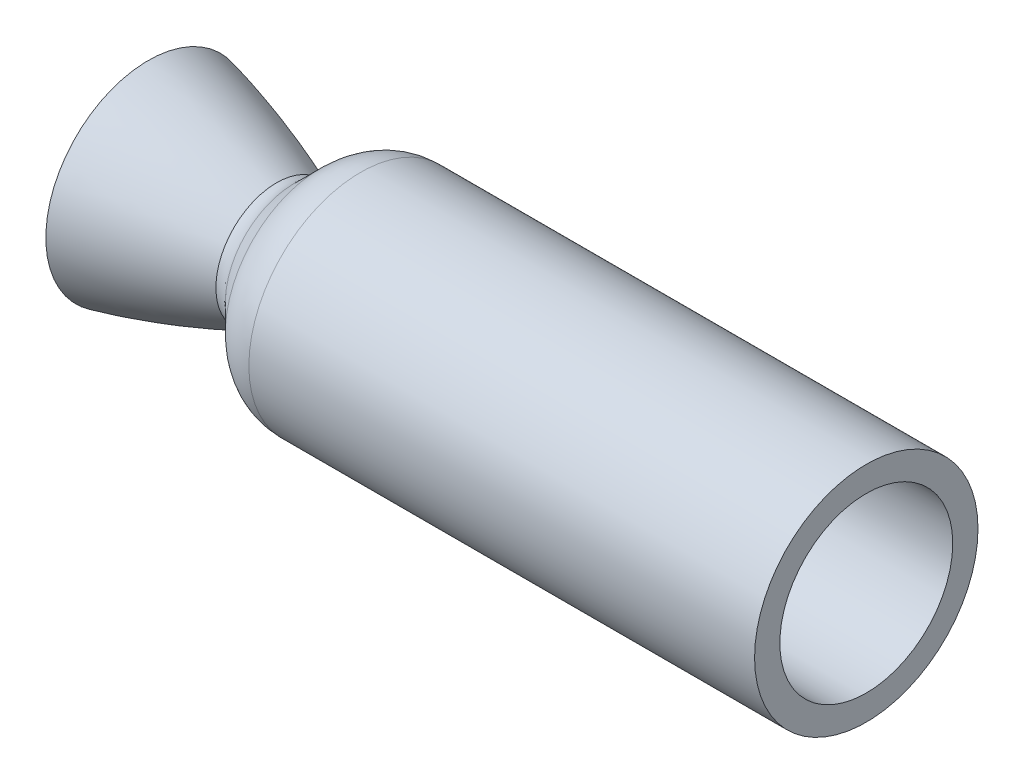
SolidWorks part; units mm, degrees
material "Thornel Mat VMA"
ref_plane "Front Plane" through (0, 0, 0) normal (0, 0, 1) x (1, 0, 0)
ref_plane "Top Plane" through (0, 0, 0) normal (0, 1, 0) x (1, 0, 0)
ref_plane "Right Plane" through (0, 0, 0) normal (1, 0, 0) x (0, 0, -1)
sketch "Sketch1" plane through (0, 0, 0) normal (0, 0, 1) x (1, 0, 0)
  line L0 (189.133, 27.386) -> (28.9492, 27.386)
  line L1 (21.8782, 24.4571) -> (13.5417, 16.1206)
  line L3 (0, 0) -> (-234.9488, 0) construction
  line L8 (189.133, 35.386) -> (28.9492, 35.386)
  line L12 (16.2213, 30.1139) -> (7.8848, 21.7775)
  line L13 (189.133, 27.386) -> (189.133, 35.386)
  line L14 (-40.127, 24.64) -> (-38.315, 32.4321)
  arc A0 (28.9492, 27.386) -> (21.8782, 24.4571) centre (28.9492, 17.386) ccw
  arc A4 (28.9492, 35.386) -> (16.2213, 30.1139) centre (28.9492, 17.386) ccw
  arc A7 (2.3482, 19.2268) -> (2.3482, 19.2268) centre (2.3482, 19.2268) cw
  arc A8 (7.8848, 21.7775) -> (2.3482, 19.2268) centre (1.6623, 28) cw construction
  arc A9 (2.3482, 19.2268) -> (7.8848, 21.7775) centre (1.6623, 28) ccw
  arc A10 (0.1069, 11.2722) -> (0, 11.5361) centre (3.1693, 12.6659) cw construction
  arc A11 (13.5417, 16.1206) -> (0.1069, 11.2722) centre (1.6623, 28) cw construction
  arc A12 (13.5417, 16.1206) -> (1.6623, 11.2) centre (1.6623, 28) cw
  arc A13 (1.6623, 11.2) -> (0, 11.5361) centre (1.6623, 15.4784) cw
  spline S0 degree 2 poles (0, 11.5361) (-19.9483, 19.9476) (-40.127, 24.64) knots 0 0 0 1 1 1 construction
  spline S1 degree 1 poles (2.3482, 19.2268) (-38.315, 32.4321) knots 0 0 1 1 construction
  spline S2 degree 2 poles (0, 11.5361) (-19.9483, 19.9476) (-40.127, 24.64) knots 0 0 0 1 1 1
  spline S3 degree 2 poles (2.3482, 19.2268) (-17.8277, 27.6653) (-38.315, 32.4321) knots 0.018494 0.018494 0.018494 1 1 1
  dimension "D1" = 10
  dimension "D4" = 16.8
  dimension "D5" = 4.2784
  dimension "D14" = 27.386
  dimension "D16" = 167.2548
  dimension "D2" = 11.2
  dimension "D6" = 45
  dimension "D7" = 24.64
  dimension "D3" = 8
revolve "Revolve1" add sketch "Sketch1" angle 360 about L3
equation "\"theta_t\"= 36.9009 - ( 426.271 / ( \"Aet\" + 7.00037 ) ) + ( 10026.8 / ( \"Aet\" + 7.00037 ) ^ 2 ) - ( 175410 / ( \"Aet\" + 7.00037 ) ^ 3 ) + ( ( 1.6742 * ( 10 ^ 6 ) ) / ( \"Aet\" + 7.00037 ) ^ 4 ) - ( ( 6.7643 * ( 10 ^ 6 ) ) / ( \"Aet\" + 7.00037 ) ^ 5 )"
equation "\"rt\" = 11.2"
equation "\"re\"= sqr ( \"rt\" ^ 2 * \"Aet\" )"
equation "\"Aet\" = 4.84"
equation "\"L\"= 0.8 * ( ( \"re\" / tan ( 15 ) ) - ( \"rt\" / tan ( 15 ) ) )"
equation "\"lc\"= ( \"l*\" / \"cr\" )"
equation "\"b\"= tan ( \"theta_t\" )"
equation "\"a\"= ( \"re\" - \"b\" * \"L\" - \"c\" ) / \"L\" ^ 2"
equation "\"c\"= \"rt\" * ( 1.382 - 0.382 * cos ( \"theta_t\" ) )"
equation "\"cr\" = 5.9789"
equation "\"rc\"= sqr ( \"cr\" * ( \"rt\" ^ 2 ) )"
equation "\"D14@Sketch1\"=\"rc\""
equation "\"l*\"= 1000"
equation "\"D16@Sketch1\"=\"lc\""
equation "\"th\" = 8"
equation "\"theta_cr\"= 45deg"
equation "\"theta_e\"= 5.48 + ( 134.316 / ( \"Aet\" + 1.49269 ) ) - ( 1742.02 / ( \"Aet\" + 1.49269 ) ^ 2 ) + ( 13091 / ( \"Aet\" + 1.49269 ) ^ 3 ) - ( 41929.9 / ( \"Aet\" + 1.49269 ) ^ 4 ) + ( 44445.1 / ( \"Aet\" + 1.49269 ) ^ 5 )"
equation "\"Nx\"= 0"
equation "\"Ny\"= \"c\""
equation "\"Qx\"= ( \"re\" - ( tan ( \"theta_e\" ) * \"L\" ) - \"c\" ) / ( tan ( \"theta_t\" ) - tan ( \"theta_e\" ) )"
equation "\"Qy\"= tan ( \"theta_t\" ) * \"Qx\" + \"c\""
equation "\"Ex\"= \"L\""
equation "\"Ey\"= \"re\""
equation "\"D3@Sketch1\"=\"th\""
equation "\"D2@Sketch1\"=\"rt\""
equation "\"D4@Sketch1\"=\"rt\"*1.5"
equation "\"D5@Sketch1\"=\"rt\"*0.382"
equation "\"D6@Sketch1\"=\"theta_cr\""
equation "\"D7@Sketch1\"=\"re\""
